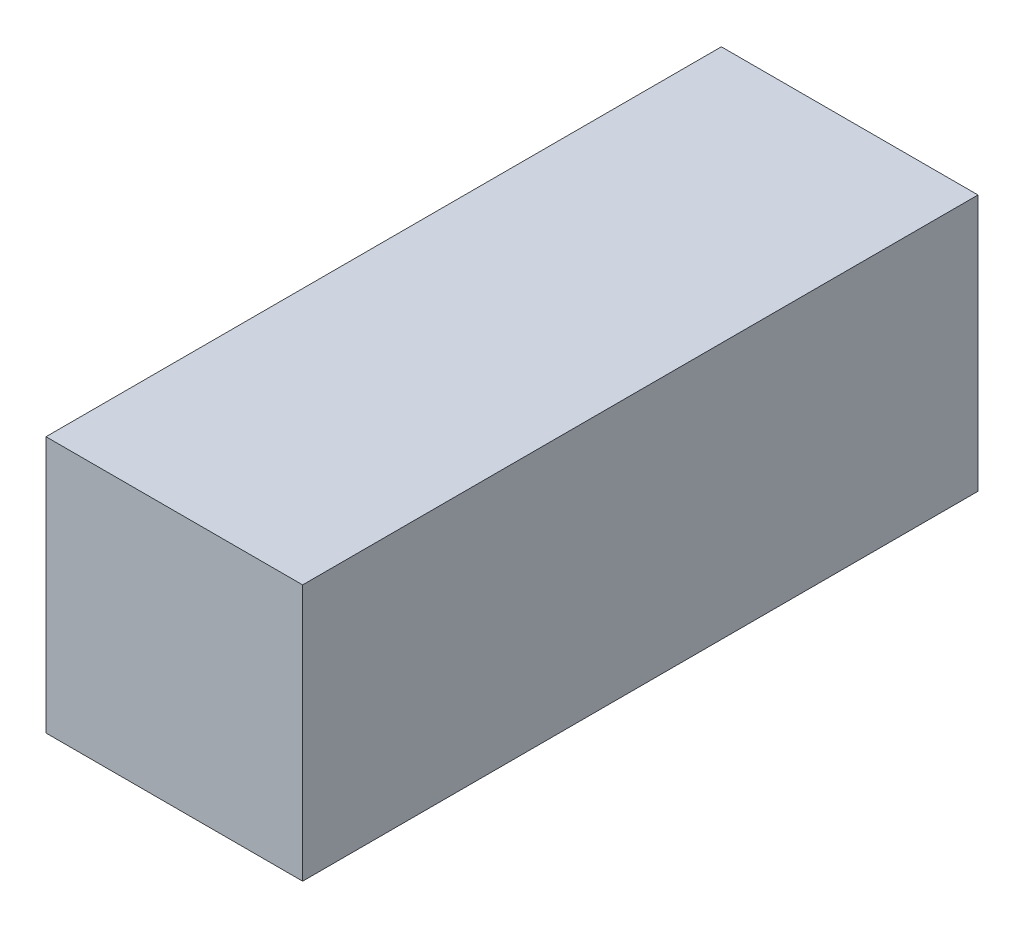
SolidWorks part; units mm, degrees
material "ぶな"
ref_plane "正面" through (0, 0, 0) normal (0, 0, 1) x (1, 0, 0)
ref_plane "平面" through (0, 0, 0) normal (0, 1, 0) x (1, 0, 0)
ref_plane "右側面" through (0, 0, 0) normal (1, 0, 0) x (0, 0, -1)
sketch "ｽｹｯﾁ1" plane through (0, 0, 0) normal (0, 0, 1) x (1, 0, 0)
  line L1 (19, 19) -> (-19, 19)
  line L2 (19, 19) -> (19, -19)
  line L3 (19, -19) -> (-19, -19)
  line L4 (-19, 19) -> (-19, -19)
  line L5 (19, 19) -> (-19, -19) construction
  line L6 (19, -19) -> (-19, 19) construction
  point P0 (0, 0)
  dimension "D1" = 38
  dimension "D2" = 38
extrude "ﾎﾞｽ - 押し出し1" add sketch "ｽｹｯﾁ1" along normal blind 100
